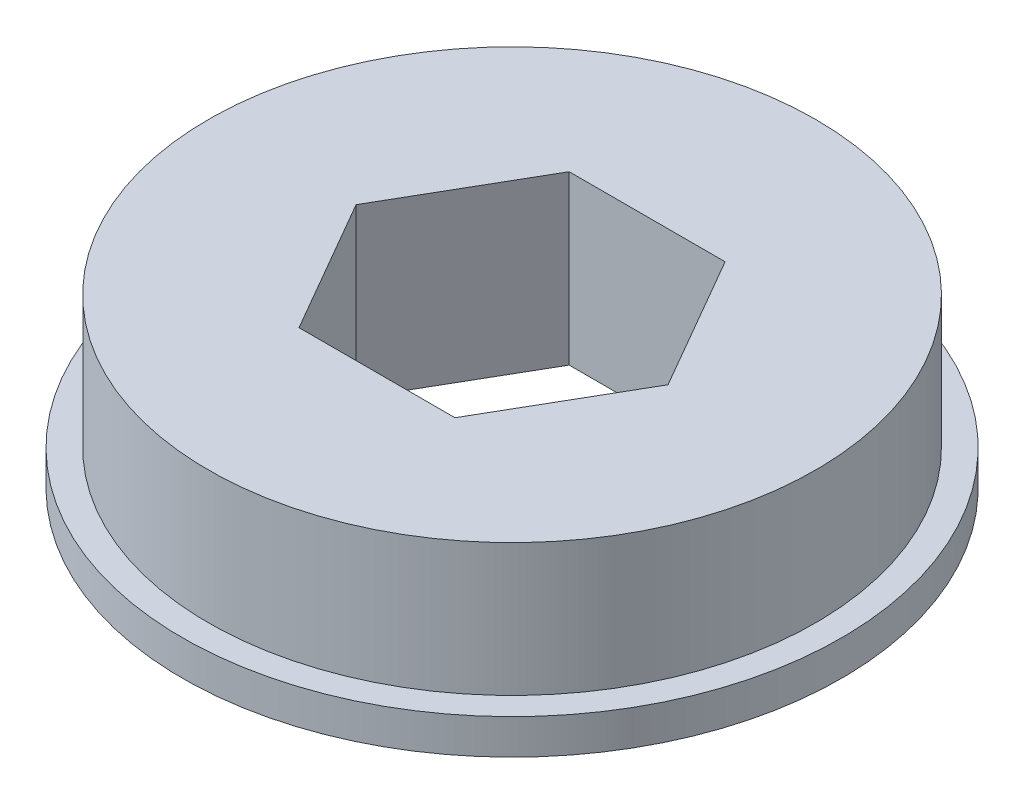
SolidWorks part; units mm, degrees
ref_plane "Front Plane" through (0, 0, 0) normal (0, 0, 1) x (1, 0, 0)
ref_plane "Top Plane" through (0, 0, 0) normal (0, 1, 0) x (1, 0, 0)
ref_plane "Right Plane" through (0, 0, 0) normal (1, 0, 0) x (0, 0, -1)
sketch "Sketch3" plane through (0, 0, 0) normal (1, 0, 0) x (0, 0, -1)
  line L0 (0, 0) -> (0, 13.4547) construction
  line L1 (0, 7.874) -> (14.2748, 7.874)
  line L2 (14.2748, 7.874) -> (14.2748, 1.651)
  line L3 (14.2748, 1.651) -> (15.494, 1.651)
  line L4 (15.494, 1.651) -> (15.494, 0)
  line L5 (15.494, 0) -> (0, 0)
  line L6 (0, 0) -> (0, 7.874)
  dimension "D1" = 7.874
  dimension "D2" = 1.651
  dimension "D3" = 30.988
  dimension "D4" = 28.5496
revolve "Revolve1" add sketch "Sketch3" angle 360 about L0
sketch "Sketch4" plane through (0, 7.874, 0) normal (0, 1, 0) x (1, 0, 0)
  line L1 (-3.6662, 6.35) -> (-7.3323, 0)
  line L2 (-7.3323, 0) -> (-3.6662, -6.35)
  line L3 (-3.6662, -6.35) -> (3.6662, -6.35)
  line L4 (3.6662, -6.35) -> (7.3323, 0)
  line L5 (7.3323, 0) -> (3.6662, 6.35)
  line L6 (3.6662, 6.35) -> (-3.6662, 6.35)
  circle A0 centre (0, 0) radius 6.35 construction
  point P1 (0, 0)
  dimension "D1" = 12.7
extrude "Cut-Extrude1" cut sketch "Sketch4" against normal through all
